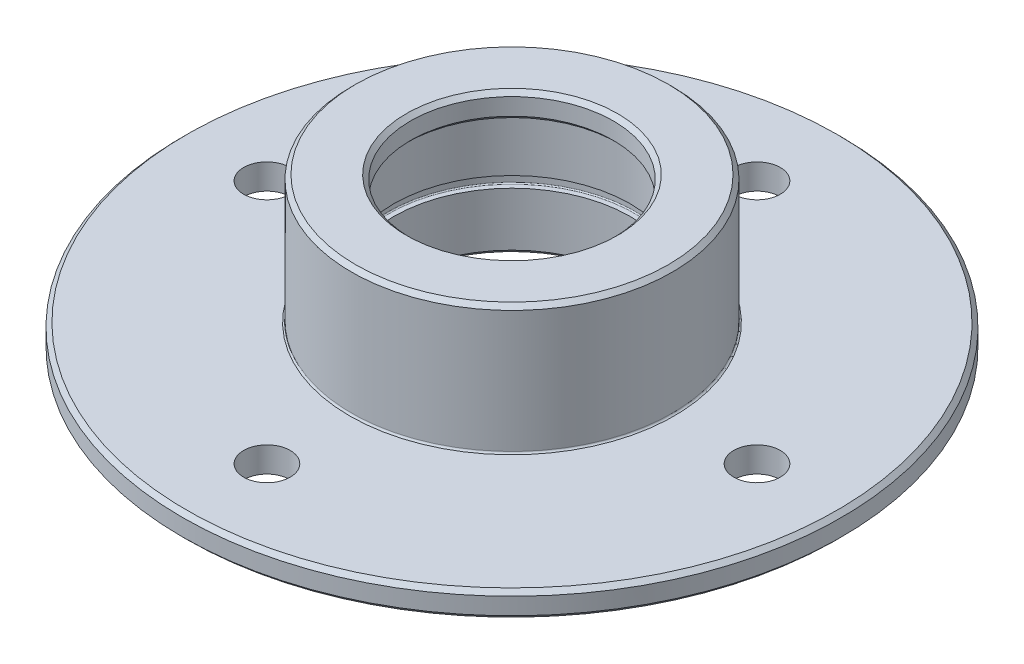
SolidWorks part; units mm, degrees
ref_plane "Front" through (0, 0, 0) normal (0, 0, 1) x (1, 0, 0)
ref_plane "Top" through (0, 0, 0) normal (0, 1, 0) x (1, 0, 0)
ref_plane "Right" through (0, 0, 0) normal (1, 0, 0) x (0, 0, -1)
sketch "Sketch1" plane through (0, 0, 0) normal (0, 0, 1) x (1, 0, 0)
  line L0 (0, 17.954) -> (0, -17.7415) construction
  line L2 (14, -3) -> (14, 12.15)
  line L4 (19, 15.15) -> (19, 0)
  line L5 (19, 0) -> (39, 0)
  line L6 (39, 0) -> (39, -3)
  line L7 (39, -3) -> (14, -3)
  line L9 (19, 15.15) -> (12, 15.15)
  line L10 (12, 15.15) -> (12, 12.15)
  line L11 (12, 12.15) -> (14, 12.15)
  line L12 (-12.05, 5.15) -> (12.05, 5.15) construction
  dimension "D1" = 5
  dimension "D2" = 14
  dimension "D3" = 12
  dimension "D4" = 20
  dimension "D5" = 3
  dimension "D6" = 3
  dimension "D7" = 7
revolve "Revolve1" add sketch "Sketch1" angle 360 about L0
sketch "Sketch2" [suppressed] plane through (0, 0, 0) normal (0, 1, 0) x (1, 0, 0)
  circle A0 centre (0, 0) radius 11
extrude "Cut-Extrude1" [suppressed] cut sketch "Sketch2" against normal through all
ref_plane "Plane1" through (0, 17.954, 0) normal (-1, 0, 0) x (0, 0, 1)
hole_wizard "M5 Clearance Hole1" positions "Sketch5" profile "Sketch6" hole size "M5" standard "ISO" end condition through all
sketch "Sketch5" plane through (0, 0, 0) normal (0, 1, 0) x (1, 0, 0)
  circle A0 centre (0, 0) radius 29 construction
  point P0 (0, 29)
  point P7 (29, 0)
  point P9 (0, -29)
  point P11 (-29, 0)
  dimension "D1" = 58
sketch "Sketch6" plane through (0, 0, -29) normal (1, 0, 0) x (0, 0, 1)
  line L0 (0, 0) -> (0, 3)
  line L1 (0, 3) -> (2.75, 3)
  line L2 (2.75, 3) -> (2.75, 0)
  line L5 (2.75, 0) -> (0, 0)
  line L11 (0, -6.35) -> (0, 107.95) construction
  dimension "Thru Hole Dia." = 5.5
  dimension "Thru Hole Depth" = 3
fillet "Fillet1" radius 0.2 2 edges at (0, 0, 19) (0, 12.15, 14)
chamfer "Chamfer1" distance 0.5 angle 45 6 edges at (0, -3, 14) (0, 15.15, 19) (0, 15.15, 12) (0, 12.15, 12) (0, -3, 39) (0, 0, 39)
ref_plane "Plane2" through (0, 17.954, 0) normal (-1, 0, 0) x (0, 0, 1)
ref_plane "Plane3" through (0, 17.954, 0) normal (-1, 0, 0) x (0, 0, 1)
ref_plane "Plane4" through (0, 17.954, 0) normal (-1, 0, 0) x (0, 0, 1)
ref_plane "Plane5" through (0, 17.954, 0) normal (-1, 0, 0) x (0, 0, 1)
sketch "Sketch14" plane through (0, 17.954, 0) normal (-1, 0, 0) x (0, 0, 1)
  line L0 (14.57, -14.104) -> (12.6, -14.104)
  line L1 (12.6, -14.104) -> (12.6, -12.804)
  line L2 (12.6, -12.804) -> (14.57, -12.804)
  line L3 (14.7, -12.934) -> (14.7, -13.974)
  line L4 (0, -50) -> (0, 50) construction
  line L5 (-12.5, -5.804) -> (12.5, -5.804) construction
  arc A0 (14.7, -13.974) -> (14.57, -14.104) centre (14.57, -13.974) cw
  arc A1 (14.7, -12.934) -> (14.57, -12.804) centre (14.57, -12.934) ccw
  dimension "D1" = 0.13
  dimension "D2" = 0.13
  dimension "D3" = 7
  dimension "D4" = 1.3
  dimension "D5" = 1.97
  dimension "D6" = 12.6
revolve "Groove for BS 3673 P4 - B028M, Internal Circlip1" cut sketch "Sketch14"
